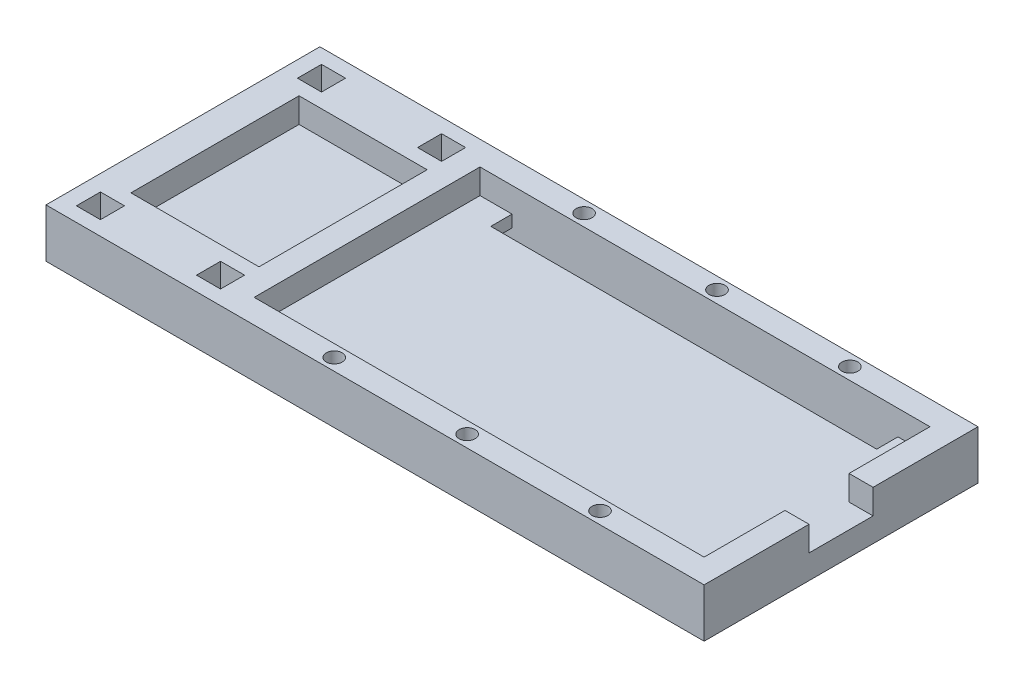
SolidWorks part; units mm, degrees
ref_plane "Front Plane" through (0, 0, 0) normal (0, 0, 1) x (1, 0, 0)
ref_plane "Top Plane" through (0, 0, 0) normal (0, 1, 0) x (1, 0, 0)
ref_plane "Right Plane" through (0, 0, 0) normal (1, 0, 0) x (0, 0, -1)
sketch "Sketch1" plane through (0, 0, 0) normal (0, 1, 0) x (1, 0, 0)
  line L1 (23.2, -12.375) -> (-23.2, -12.375)
  line L2 (23.2, -12.375) -> (23.2, 12.375)
  line L3 (23.2, 12.375) -> (-23.2, 12.375)
  line L4 (-23.2, -12.375) -> (-23.2, 12.375)
  line L5 (23.2, -12.375) -> (-23.2, 12.375) construction
  line L6 (23.2, 12.375) -> (-23.2, -12.375) construction
  point P0 (0, 0)
  dimension "D1" = 24.75
  dimension "D2" = 46.4
extrude "Boss-Extrude1" add sketch "Sketch1" along normal blind 5.9
sketch "Sketch2" plane through (0, 5.9, 0) normal (0, 1, 0) x (1, 0, 0)
  line L0 (23.2, 0) -> (23.2, 11.45)
  line L1 (23.2, -12.375) -> (23.2, 12.375) construction
  line L2 (23.2, 0) -> (23.2, -11.45)
  line L3 (23.2, -11.45) -> (23.2, 11.45)
  line L4 (23.2, -11.45) -> (-23.2, -11.45)
  line L5 (23.2, 11.45) -> (-23.2, 11.45)
  line L6 (-23.2, -11.45) -> (-23.2, 11.45)
  line M4 (-23.2, 12.375) -> (-23.2, -12.375)
  line M6 (23.2, -12.375) -> (23.2, 12.375)
  dimension "D1" = 11.45
  dimension "D2" = 11.45
  dimension "D3" = 46.4
extrude "Boss-Extrude2" add sketch "Sketch2" along normal blind 2.5 contours L5 L4 M6 M4
sketch "Sketch3" plane through (0, 0, 0) normal (0, -1, 0) x (1, 0, 0)
  line L1 (-25, 25) -> (25, 25)
  line L2 (-25, 25) -> (-25, -25)
  line L3 (-25, -25) -> (25, -25)
  line L4 (25, 25) -> (25, -25)
  line L5 (-25, 25) -> (25, -25) construction
  line L6 (-25, -25) -> (25, 25) construction
  point P0 (0, 0)
  dimension "D1" = 50
  dimension "D2" = 50
extrude "Boss-Extrude3" add sketch "Sketch3" along normal blind 2.5
sketch "Sketch4" plane through (0, 0, 0) normal (0, 1, 0) x (1, 0, 0)
  line L1 (-23.2, 12.375) -> (-23.2, 13.175)
  line L3 (23.2, 12.375) -> (23.2, 13.175)
  line L4 (23.2, 13.175) -> (-23.2, 13.175)
  line L5 (23.2, 13.175) -> (23.2, 15.175)
  line L6 (-23.2, 13.175) -> (-23.2, 15.175)
  line L7 (23.2, 15.175) -> (-23.2, 15.175)
  line L8 (23.2, 13.175) -> (-23.2, 13.175)
  line L9 (23.2, 13.175) -> (23.2, 14.105)
  line L10 (-23.2, 13.175) -> (-23.2, 14.105)
  line L11 (23.2, 14.105) -> (-23.2, 14.105)
  dimension "D1" = 0.8
  dimension "D2" = 2
  dimension "D3" = 0.93
extrude "Boss-Extrude4" add sketch "Sketch4" along normal up to surface (5.9 mm away) contours L5 L11 L6 L4 up to face at (0, 5.9, -11.9125)
sketch "Sketch5" plane through (0, 0, 0) normal (0, 1, 0) x (1, 0, 0)
  line L0 (-23.2, -12.375) -> (-23.2, -13.175)
  line L1 (23.2, -12.375) -> (23.2, -13.175)
  line L2 (23.2, -13.175) -> (-23.2, -13.175)
  line L3 (23.2, -13.175) -> (23.2, -14.105)
  line L4 (-23.2, -13.175) -> (-23.2, -14.105)
  line L5 (23.2, -14.105) -> (-23.2, -14.105)
  dimension "D1" = 0.8
  dimension "D2" = 0.93
extrude "Boss-Extrude5" add sketch "Sketch5" along normal up to surface (5.9 mm away) contours L5 L3 L2 L4 up to face at (0, 5.9, 11.9125)
sketch "Sketch6" plane through (0, 0, 0) normal (0, 1, 0) x (1, 0, 0)
  line L0 (-23.2, 14.105) -> (23.2, 14.105)
  line L1 (-23.2, 14.105) -> (-23.2, 17.105)
  line L2 (23.2, 14.105) -> (23.2, 17.105)
  line L3 (-23.2, 17.105) -> (23.2, 17.105)
  dimension "D1" = 3
extrude "Boss-Extrude6" add sketch "Sketch6" along normal up to surface (8.4 mm away) up to face at (0, 8.4, 0)
sketch "Sketch7" plane through (0, 0, 0) normal (0, 1, 0) x (1, 0, 0)
  line L0 (23.2, -14.105) -> (-23.2, -14.105)
  line L1 (23.2, -14.105) -> (23.2, -17.105)
  line L2 (-23.2, -14.105) -> (-23.2, -17.105)
  line L3 (23.2, -17.105) -> (-23.2, -17.105)
  dimension "D1" = 3
extrude "Boss-Extrude7" add sketch "Sketch7" along normal up to surface (8.4 mm away) up to face at (0, 8.4, 0)
sketch "Sketch8" plane through (0, 8.4, 0) normal (0, 1, 0) x (1, 0, 0)
  line L0 (-23.2, 11.45) -> (-23.2, -11.45)
  line L1 (-23.2, 11.45) -> (23.2, 11.45)
  line L2 (-23.2, -11.45) -> (23.2, -11.45)
  line L3 (23.2, 11.45) -> (23.2, -11.45)
  line L4 (23.2, -11.45) -> (23.2, 11.45) construction
  dimension "D1" = 0
extrude "Boss-Extrude8" add sketch "Sketch8" along normal blind 8.4
sketch "Sketch9" plane through (0, 8.4, 0) normal (0, 1, 0) x (1, 0, 0)
  line L0 (-23.2, -14.105) -> (-23.2, -17.105)
  line L1 (-23.2, -14.105) -> (23.2, -14.105)
  line L2 (-23.2, -17.105) -> (23.2, -17.105)
  line L3 (23.2, -14.105) -> (23.2, -17.105)
  line L4 (23.2, -17.105) -> (23.2, -14.105) construction
  dimension "D1" = 0
extrude "Boss-Extrude9" add sketch "Sketch9" along normal blind 8.4
sketch "Sketch10" plane through (23.2, 0, 0) normal (1, 0, 0) x (0, 0, -1)
  line L0 (-11.45, 16.8) -> (-11.45, 5.9)
  line L1 (-11.45, 16.8) -> (11.45, 16.8)
  line L2 (-11.45, 5.9) -> (11.45, 5.9)
  line L3 (11.45, 16.8) -> (11.45, 5.9)
  line L4 (-12.375, 5.9) -> (-12.375, 0)
  line L5 (-12.375, 5.9) -> (12.375, 5.9)
  line L6 (-12.375, 0) -> (12.375, 0)
  line L7 (12.375, 5.9) -> (12.375, 0)
  line L8 (12.375, 5.9) -> (12.375, 0) construction
  line L9 (11.45, 16.8) -> (11.45, 5.9) construction
  line M3 (-12.375, 0) -> (12.375, 0)
  line M4 (12.375, 0) -> (12.375, 5.9)
  line M5 (12.375, 5.9) -> (11.45, 5.9)
  line M6 (11.45, 5.9) -> (11.45, 16.8)
  line M7 (11.45, 16.8) -> (-11.45, 16.8)
  line M8 (-11.45, 16.8) -> (-11.45, 5.9)
  line M9 (-11.45, 5.9) -> (-12.375, 5.9)
  line M10 (-12.375, 5.9) -> (-12.375, 0)
  dimension "D1" = 0
  dimension "D2" = 0
extrude "Boss-Extrude10" add sketch "Sketch10" along normal up to surface (1.8 mm away) contours L2 M8 M6 M7 | L2 M9 M10 M3 M4 M5 up to face at (25, -1.25, 0)
sketch "Sketch11" plane through (23.2, 0, 0) normal (1, 0, 0) x (0, 0, -1)
  line L0 (-17.105, 16.8) -> (-14.105, 16.8)
  line L1 (-17.105, 16.8) -> (-17.105, 0)
  line L2 (-14.105, 16.8) -> (-14.105, 0)
  line L3 (-17.105, 0) -> (-14.105, 0)
  line L4 (-13.175, 0) -> (-17.105, 0) construction
  line L5 (-13.175, 5.9) -> (-14.105, 5.9)
  line L6 (-13.175, 5.9) -> (-13.175, 0)
  line L7 (-14.105, 5.9) -> (-14.105, 0)
  line L8 (-13.175, 0) -> (-14.105, 0)
  line M3 (-13.175, 0) -> (-13.175, 5.9)
  line M4 (-13.175, 5.9) -> (-14.105, 5.9)
  line M5 (-14.105, 5.9) -> (-14.105, 16.8)
  line M6 (-14.105, 16.8) -> (-17.105, 16.8)
  line M7 (-17.105, 16.8) -> (-17.105, 0)
  line M8 (-17.105, 0) -> (-13.175, 0)
  dimension "D1" = 0
  dimension "D2" = 0
extrude "Boss-Extrude11" add sketch "Sketch11" along normal up to surface (1.8 mm away) contours L2 M5 M6 M7 M8 | L2 M4 M8 M3 up to face at (25, 4.35, 0)
sketch "Sketch12" plane through (0, 5.9, 0) normal (0, 1, 0) x (1, 0, 0)
  line L0 (-23.2, -11.45) -> (-23.2, -12.375)
  line L1 (-23.2, -11.45) -> (9.5, -11.45)
  line L2 (-23.2, -12.375) -> (9.5, -12.375)
  line L3 (9.5, -11.45) -> (9.5, -12.375)
  line L4 (25, -11.45) -> (25, -12.375) construction
  line L5 (-23.2, -13.175) -> (-23.2, -14.105)
  line L6 (-23.2, -13.175) -> (9.5, -13.175)
  line L7 (-23.2, -14.105) -> (9.5, -14.105)
  line L8 (9.5, -13.175) -> (9.5, -14.105)
  line L9 (25, -14.105) -> (25, -13.175) construction
  dimension "D1" = 15.5
  dimension "D2" = 15.5
extrude "Boss-Extrude12" add sketch "Sketch12" along normal blind 8.4
sketch "Sketch13" plane through (23.2, 0, 0) normal (1, 0, 0) x (0, 0, -1)
  line L0 (17.105, 8.4) -> (14.105, 8.4)
  line L1 (17.105, 8.4) -> (17.105, 0)
  line L2 (14.105, 8.4) -> (14.105, 0)
  line L3 (17.105, 0) -> (14.105, 0)
  line L4 (13.175, 0) -> (17.105, 0) construction
  line L5 (14.105, 5.9) -> (13.175, 5.9)
  line L6 (14.105, 5.9) -> (14.105, 0)
  line L7 (13.175, 5.9) -> (13.175, 0)
  line L8 (14.105, 0) -> (13.175, 0)
  line M3 (14.105, 5.9) -> (13.175, 5.9)
  line M4 (13.175, 5.9) -> (13.175, 0)
  line M5 (13.175, 0) -> (17.105, 0)
  line M6 (17.105, 0) -> (17.105, 8.4)
  line M7 (17.105, 8.4) -> (14.105, 8.4)
  line M8 (14.105, 8.4) -> (14.105, 5.9)
  dimension "D1" = 0
  dimension "D2" = 0
extrude "Boss-Extrude13" add sketch "Sketch13" along normal up to surface (1.8 mm away) contours L2 M8 M5 M6 M7 | L2 M3 M4 M5 up to face at (25, 5.4222, 4.9317)
sketch "Sketch14" plane through (0, 8.4, 0) normal (0, 1, 0) x (1, 0, 0)
  line L0 (-23.2, 17.105) -> (-23.2, 14.105)
  line L1 (-23.2, 17.105) -> (25, 17.105)
  line L2 (-23.2, 14.105) -> (25, 14.105)
  line L3 (25, 17.105) -> (25, 14.105)
  line L4 (25, 14.105) -> (25, 17.105) construction
  dimension "D1" = 0
extrude "Boss-Extrude14" add sketch "Sketch14" along normal blind 8.4
sketch "Sketch15" plane through (0, 5.9, 0) normal (0, 1, 0) x (1, 0, 0)
  line L0 (25, 14.105) -> (25, 13.175)
  line L1 (25, 14.105) -> (-7.7, 14.105)
  line L2 (25, 13.175) -> (-7.7, 13.175)
  line L3 (-7.7, 14.105) -> (-7.7, 13.175)
  line L4 (-23.2, 13.175) -> (-23.2, 14.105) construction
  line L5 (25, 12.375) -> (25, 11.45)
  line L6 (25, 12.375) -> (-7.7, 12.375)
  line L7 (25, 11.45) -> (-7.7, 11.45)
  line L8 (-7.7, 12.375) -> (-7.7, 11.45)
  line L9 (-23.2, 12.375) -> (-23.2, 11.45) construction
  dimension "D1" = 15.5
  dimension "D2" = 15.5
extrude "Boss-Extrude15" add sketch "Sketch15" along normal blind 8.4
sketch "Sketch16" plane through (25, 0, 0) normal (1, 0, 0) x (0, 0, -1)
  line L0 (-12.775, 0) -> (-12.025, 0)
  line L1 (-12.375, 0) -> (-13.175, 0) construction
  line L2 (-12.775, 0) -> (-13.525, 0)
  line L3 (-12.025, 0) -> (-13.525, 0)
  line L4 (-12.025, 0) -> (-12.025, 5.9)
  line L5 (-13.525, 0) -> (-13.525, 5.9)
  line L6 (-12.025, 5.9) -> (-13.525, 5.9)
  line L7 (-11.45, 5.9) -> (-12.375, 5.9) construction
  line M15 (-11.45, 5.9) -> (-12.375, 5.9)
  line M16 (-12.375, 5.9) -> (-12.375, 0)
  line M18 (-13.175, 0) -> (-13.175, 5.9)
  line M19 (-13.175, 5.9) -> (-14.105, 5.9)
  dimension "D1" = 0.75
  dimension "D2" = 0
extrude "Cut-Extrude1" cut sketch "Sketch16" against normal through all contours L0 L4 M15 M16 | L5 L2 M18 M19
sketch "Sketch18" plane through (25, 0, 0) normal (1, 0, 0) x (0, 0, -1)
  line L0 (12.775, 0) -> (13.525, 0)
  line L1 (13.175, 0) -> (12.375, 0) construction
  line L2 (12.775, 0) -> (12.025, 0)
  line L3 (12.025, 0) -> (13.525, 0)
  line L4 (12.025, 0) -> (12.025, 5.9)
  line L5 (13.525, 0) -> (13.525, 5.9)
  line L6 (12.025, 5.9) -> (13.525, 5.9)
  line L7 (12.375, 5.9) -> (11.45, 5.9) construction
  line M19 (13.175, 14.3) -> (13.175, 0)
  line M21 (12.375, 0) -> (12.375, 14.3)
  dimension "D1" = 0.75
  dimension "D2" = 0
extrude "Cut-Extrude2" cut sketch "Sketch18" against normal through all contours L6 L4 L2 M21 | L6 L0 L5 M19
sketch "Sketch20" plane through (-23.2, 0, 0) normal (-1, 0, 0) x (0, 0, 1)
  line L0 (11.45, 16.8) -> (11.45, 14.3)
  line L1 (11.45, 16.8) -> (-11.45, 16.8)
  line L2 (11.45, 14.3) -> (-11.45, 14.3)
  line L3 (-11.45, 16.8) -> (-11.45, 14.3)
  line L4 (-11.45, 16.8) -> (-11.45, 5.9) construction
  dimension "D1" = 0
extrude "Boss-Extrude17" add sketch "Sketch20" along normal blind 4
sketch "Sketch22" plane through (-27.2, 0, 0) normal (-1, 0, 0) x (0, 0, 1)
  line L0 (11.45, 16.8) -> (11.45, 14.3)
  line L1 (11.45, 16.8) -> (-11.45, 16.8)
  line L2 (11.45, 14.3) -> (-11.45, 14.3)
  line L3 (-11.45, 16.8) -> (-11.45, 14.3)
  line L4 (-11.45, 16.8) -> (-11.45, 14.3) construction
  dimension "D1" = 0
extrude "Boss-Extrude19" add sketch "Sketch22" along normal blind 3
sketch "Sketch23" plane through (0, 16.8, 0) normal (0, 1, 0) x (1, 0, 0)
  line L0 (-30.2, -11.45) -> (-30.2, 11.45)
  line L1 (-30.2, -11.45) -> (-27.2, -11.45)
  line L2 (-30.2, 11.45) -> (-27.2, 11.45)
  line L3 (-27.2, -11.45) -> (-27.2, 11.45)
  dimension "D1" = 3
extrude "Boss-Extrude20" add sketch "Sketch23" along normal blind 1.5
sketch "Sketch24" plane through (25, 0, 0) normal (1, 0, 0) x (0, 0, -1)
  line L0 (11.45, 16.8) -> (11.45, 14.3)
  line L1 (11.45, 16.8) -> (-11.45, 16.8)
  line L2 (11.45, 14.3) -> (-11.45, 14.3)
  line L3 (-11.45, 16.8) -> (-11.45, 14.3)
  line L4 (-11.45, 5.9) -> (-11.45, 16.8) construction
  dimension "D1" = 0
extrude "Boss-Extrude21" add sketch "Sketch24" along normal blind 7
sketch "Sketch25" plane through (0, 16.8, 0) normal (0, 1, 0) x (1, 0, 0)
  line L0 (32, -11.45) -> (29, -11.45)
  line L1 (32, -11.45) -> (32, 11.45)
  line L2 (29, -11.45) -> (29, 11.45)
  line L3 (32, 11.45) -> (29, 11.45)
  line L4 (-27.2, -11.45) -> (32, -11.45) construction
  line L5 (32, 11.45) -> (-27.2, 11.45) construction
  dimension "D1" = 3
  dimension "D2" = 0
extrude "Boss-Extrude22" add sketch "Sketch25" along normal blind 3
sketch "Sketch27" plane through (0, 16.8, 0) normal (0, 1, 0) x (1, 0, 0)
  line L0 (25, 17.105) -> (25, 14.105)
  line L1 (25, 17.105) -> (-23.2, 17.105)
  line L2 (25, 14.105) -> (-23.2, 14.105)
  line L3 (-23.2, 17.105) -> (-23.2, 14.105)
  line L4 (-23.2, 17.105) -> (-23.2, 14.105) construction
  line L5 (25, -14.105) -> (25, -17.105)
  line L6 (25, -14.105) -> (-23.2, -14.105)
  line L7 (25, -17.105) -> (-23.2, -17.105)
  line L8 (-23.2, -14.105) -> (-23.2, -17.105)
  line L9 (-23.2, -14.105) -> (-23.2, -17.105) construction
  dimension "D1" = 0
  dimension "D2" = 0
extrude "Boss-Extrude23" add sketch "Sketch27" along normal blind 7
sketch "Sketch28" plane through (0, 16.8, 0) normal (0, 1, 0) x (1, 0, 0)
  line L0 (29, 11.45) -> (29, -11.45)
  line L1 (29, 11.45) -> (-27.2, 11.45)
  line L2 (29, -11.45) -> (-27.2, -11.45)
  line L3 (-27.2, 11.45) -> (-27.2, -11.45)
  line L4 (-27.2, -11.45) -> (-27.2, 11.45) construction
  dimension "D1" = 0
extrude "Boss-Extrude24" add sketch "Sketch28" along normal blind 7
sketch "Sketch29" plane through (0, 18.3, 0) normal (0, 1, 0) x (1, 0, 0)
  line L0 (-30.2, 11.45) -> (-27.2, 11.45)
  line L1 (-30.2, 11.45) -> (-30.2, -11.45)
  line L2 (-27.2, 11.45) -> (-27.2, -11.45)
  line L3 (-30.2, -11.45) -> (-27.2, -11.45)
  line L4 (-30.2, -11.45) -> (-27.2, -11.45) construction
  point P8 (-28.7, -11.45)
  dimension "D1" = 0
extrude "Boss-Extrude25" add sketch "Sketch29" along normal blind 7
sketch "Sketch30" plane through (0, 19.8, 0) normal (0, 1, 0) x (1, 0, 0)
  line L0 (32, 11.45) -> (29, 11.45)
  line L1 (32, 11.45) -> (32, -11.45)
  line L2 (29, 11.45) -> (29, -11.45)
  line L3 (32, -11.45) -> (29, -11.45)
  line L4 (29, -11.45) -> (32, -11.45) construction
  dimension "D1" = 0
extrude "Boss-Extrude26" add sketch "Sketch30" along normal blind 7
sketch "Sketch31" plane through (0, 0, -11.45) normal (0, 0, -1) x (-1, 0, 0)
  line L0 (30.2, 14.3) -> (23.2, 14.3)
  line L1 (30.2, 14.3) -> (30.2, 20.8)
  line L2 (23.2, 14.3) -> (23.2, 20.8)
  line L3 (30.2, 20.8) -> (23.2, 20.8)
  line L4 (-29, 23.8) -> (27.2, 23.8) construction
  dimension "D1" = 3
extrude "Cut-Extrude3" cut sketch "Sketch31" against normal through all
sketch "Sketch32" plane through (0, 0, 11.45) normal (0, 0, 1) x (1, 0, 0)
  line L0 (25, 14.3) -> (32, 14.3)
  line L1 (25, 14.3) -> (25, 20.8)
  line L2 (32, 14.3) -> (32, 20.8)
  line L3 (25, 20.8) -> (32, 20.8)
  line L4 (-27.2, 23.8) -> (29, 23.8) construction
  dimension "D1" = 3
extrude "Cut-Extrude4" cut sketch "Sketch32" against normal through all
sketch "Sketch33" plane through (-23.2, 0, 0) normal (-1, 0, 0) x (0, 0, 1)
  line L0 (-14.105, 0) -> (-11.445, 0)
  line L1 (-14.105, 0) -> (-14.105, 2.66)
  line L2 (-11.445, 0) -> (-11.445, 2.66)
  line L3 (-14.105, 2.66) -> (-11.445, 2.66)
  line L5 (25, 0) -> (-25, 0) construction
  line L6 (-14.105, 23.8) -> (-14.105, 5.9) construction
  dimension "D1" = 2.66
  dimension "D2" = 2.66
  dimension "D3" = 0
  dimension "D4" = 0
extrude "Cut-Extrude5" cut sketch "Sketch33" against normal through all
sketch "Sketch34" plane through (-23.2, 0, 0) normal (-1, 0, 0) x (0, 0, 1)
  line L0 (11.445, 0) -> (14.105, 0)
  line L1 (11.445, 0) -> (11.445, 2.66)
  line L2 (14.105, 0) -> (14.105, 2.66)
  line L3 (11.445, 2.66) -> (14.105, 2.66)
  line L4 (25, 0) -> (-25, 0) construction
  line L5 (14.105, 23.8) -> (14.105, 14.3) construction
  dimension "D1" = 2.66
  dimension "D2" = 2.66
  dimension "D3" = 0
  dimension "D4" = 0
extrude "Cut-Extrude6" cut sketch "Sketch34" against normal through all
sketch "Sketch35" plane through (0, 26.8, 0) normal (0, 1, 0) x (1, 0, 0)
  line L0 (29, 11.45) -> (32, 11.45)
  line L1 (29, 11.45) -> (29, -11.45)
  line L2 (32, 11.45) -> (32, -11.45)
  line L3 (29, -11.45) -> (32, -11.45)
  line L4 (29, -11.45) -> (32, -11.45) construction
  line L6 (37.3606, -4) -> (26.6394, -4)
  line L7 (37.3606, -4) -> (37.3606, 4)
  line L8 (37.3606, 4) -> (26.6394, 4)
  line L9 (26.6394, -4) -> (26.6394, 4)
  line L10 (37.3606, -4) -> (26.6394, 4) construction
  line L11 (37.3606, 4) -> (26.6394, -4) construction
  point P8 (32, 0)
  dimension "D1" = 0
  dimension "D2" = 8
extrude "Cut-Extrude7" cut sketch "Sketch35" against normal up to surface (3 mm away) contours L2 L8 L1 L6 up to face at (0.9, 23.8, 0)
sketch "Sketch36" plane through (0, 25.3, 0) normal (0, 1, 0) x (1, 0, 0)
  line L0 (-30.2, 11.45) -> (-27.2, 11.45)
  line L1 (-30.2, 11.45) -> (-30.2, -11.45)
  line L2 (-27.2, 11.45) -> (-27.2, -11.45)
  line L3 (-30.2, -11.45) -> (-27.2, -11.45)
  line L4 (-30.2, -11.45) -> (-27.2, -11.45) construction
  dimension "D1" = 0
extrude "Boss-Extrude27" add sketch "Sketch36" along normal up to surface (1.5 mm away) up to face at (30.5, 26.8, 7.725)
sketch "Sketch38" plane through (0, 23.8, 0) normal (0, 1, 0) x (1, 0, 0)
  line L0 (-23.2, -14.105) -> (-23.2, -17.105)
  line L1 (-23.2, -14.105) -> (25, -14.105)
  line L2 (-23.2, -17.105) -> (25, -17.105)
  line L3 (25, -14.105) -> (25, -17.105)
  line L4 (25, -17.105) -> (25, -14.105) construction
  dimension "D1" = 0
extrude "Boss-Extrude28" add sketch "Sketch38" along normal blind 3.1
sketch "Sketch39" plane through (0, 23.8, 0) normal (0, 1, 0) x (1, 0, 0)
  line L0 (-23.2, 17.105) -> (-23.2, 14.105)
  line L1 (-23.2, 17.105) -> (25, 17.105)
  line L2 (-23.2, 14.105) -> (25, 14.105)
  line L3 (25, 17.105) -> (25, 14.105)
  line L4 (25, 14.105) -> (25, 17.105) construction
  dimension "D1" = 0
extrude "Boss-Extrude29" add sketch "Sketch39" along normal blind 3.1
sketch "Sketch40" plane through (0, 26.8, 0) normal (0, 1, 0) x (1, 0, 0)
  line L0 (29, 4) -> (32, 4)
  line L1 (29, 4) -> (29, 11.45)
  line L2 (32, 4) -> (32, 11.45)
  line L3 (29, 11.45) -> (32, 11.45)
  line L4 (32, 11.45) -> (29, 11.45) construction
  line L5 (32, -11.45) -> (29, -11.45)
  line L6 (32, -11.45) -> (32, -4)
  line L7 (29, -11.45) -> (29, -4)
  line L8 (32, -4) -> (29, -4)
  line L9 (32, -4) -> (29, -4) construction
  dimension "D1" = 0
  dimension "D2" = 0
extrude "Boss-Extrude30" add sketch "Sketch40" along normal blind 0.1
sketch "Sketch41" plane through (0, 26.8, 0) normal (0, 1, 0) x (1, 0, 0)
  line L0 (-30.2, -11.45) -> (-27.2, -11.45)
  line L1 (-30.2, -11.45) -> (-30.2, 11.45)
  line L2 (-27.2, -11.45) -> (-27.2, 11.45)
  line L3 (-30.2, 11.45) -> (-27.2, 11.45)
  line L4 (-30.2, 11.45) -> (-27.2, 11.45) construction
  dimension "D1" = 0
extrude "Boss-Extrude31" add sketch "Sketch41" along normal blind 0.1
sketch "Sketch42" plane through (0, 26.9, 0) normal (0, 1, 0) x (1, 0, 0)
  line L0 (25, 14.105) -> (25, 17.105) construction
  line L1 (-23.2, -17.105) -> (25, -17.105) construction
  line L2 (-23.2, -14.105) -> (-23.2, -17.105) construction
  line L3 (-23.2, 17.105) -> (-23.2, 14.105) construction
  line L4 (25, 17.105) -> (-23.2, 17.105) construction
  line L5 (25, -17.105) -> (25, -14.105) construction
  line L6 (25, -14.105) -> (-23.2, -14.105) construction
  line L7 (-23.2, 14.105) -> (25, 14.105) construction
  circle A0 centre (-15.7, -15.605) radius 1
  circle A1 centre (-15.7, 15.605) radius 1
  circle A2 centre (17.5, -15.605) radius 1
  circle A3 centre (17.5, 15.605) radius 1
  circle A4 centre (0.9, -15.605) radius 1
  circle A5 centre (0.9, 15.605) radius 1
  dimension "D1" = 2
  dimension "D2" = 1.5
  dimension "D4" = 2
  dimension "D5" = 7.5
  dimension "D6" = 1.5
  dimension "D7" = 2
  dimension "D8" = 2
  dimension "D9" = 7.5
  dimension "D10" = 7.5
  dimension "D11" = 33.2
  dimension "D12" = 2
  dimension "D13" = 1.5
  dimension "D14" = 16.6
  dimension "D15" = 2
  dimension "D16" = 16.6
  dimension "D17" = 1.5
  dimension "D3" = 7.5
sketch "Sketch43" plane through (0, 0, 11.45) normal (0, 0, 1) x (1, 0, 0)
  line L0 (-30.2, 26.9) -> (-27.2, 26.9)
  line L1 (-30.2, 26.9) -> (-30.2, 20.8)
  line L2 (-27.2, 26.9) -> (-27.2, 20.8)
  line L3 (-30.2, 20.8) -> (-27.2, 20.8)
  line L4 (-23.2, 20.8) -> (-30.2, 20.8) construction
  dimension "D1" = 0
extrude "Boss-Extrude32" add sketch "Sketch43" along normal up to surface (5.655 mm away) up to face at (0.9, 13.45, 17.105)
sketch "Sketch44" plane through (-27.2, 0, 0) normal (1, 0, 0) x (0, 0, -1)
  line L0 (-17.105, 26.9) -> (-17.105, 20.8)
  line L1 (-17.105, 26.9) -> (-14.105, 26.9)
  line L2 (-17.105, 20.8) -> (-14.105, 20.8)
  line L3 (-14.105, 26.9) -> (-14.105, 20.8)
  line L4 (-14.105, 26.9) -> (-14.105, 14.3) construction
  dimension "D1" = 0
extrude "Boss-Extrude33" add sketch "Sketch44" along normal up to surface (4 mm away) up to face at (-23.2, 9.952, 14.403)
sketch "Sketch45" plane through (0, 0, -11.45) normal (0, 0, -1) x (-1, 0, 0)
  line L0 (30.2, 26.9) -> (27.2, 26.9)
  line L1 (30.2, 26.9) -> (30.2, 20.8)
  line L2 (27.2, 26.9) -> (27.2, 20.8)
  line L3 (30.2, 20.8) -> (27.2, 20.8)
  line L4 (30.2, 20.8) -> (23.2, 20.8) construction
  dimension "D1" = 0
extrude "Boss-Extrude34" add sketch "Sketch45" along normal up to surface (5.655 mm away) up to face at (0.9, 13.45, -17.105)
sketch "Sketch46" plane through (-27.2, 0, 0) normal (1, 0, 0) x (0, 0, -1)
  line L0 (17.105, 20.8) -> (17.105, 26.9)
  line L1 (17.105, 20.8) -> (14.105, 20.8)
  line L2 (17.105, 26.9) -> (14.105, 26.9)
  line L3 (14.105, 20.8) -> (14.105, 26.9)
  line L4 (14.105, 26.9) -> (14.105, 5.9) construction
  dimension "D1" = 0
extrude "Boss-Extrude35" add sketch "Sketch46" along normal up to surface (4 mm away) up to face at (-23.2, 8.865, -14.71)
sketch "Sketch47" plane through (0, 0, -11.45) normal (0, 0, -1) x (-1, 0, 0)
  line L0 (-29, 26.9) -> (-32, 26.9)
  line L1 (-29, 26.9) -> (-29, 20.8)
  line L2 (-32, 26.9) -> (-32, 20.8)
  line L3 (-29, 20.8) -> (-32, 20.8)
  line L4 (-32, 20.8) -> (-25, 20.8) construction
  dimension "D1" = 0
extrude "Boss-Extrude36" add sketch "Sketch47" along normal up to surface (5.655 mm away) up to face at (-9.4667, 15.9, -17.105)
sketch "Sketch48" plane through (29, 0, 0) normal (-1, 0, 0) x (0, 0, 1)
  line L0 (-17.105, 26.9) -> (-17.105, 20.8)
  line L1 (-17.105, 26.9) -> (-14.105, 26.9)
  line L2 (-17.105, 20.8) -> (-14.105, 20.8)
  line L3 (-14.105, 26.9) -> (-14.105, 20.8)
  line L4 (-14.105, 14.3) -> (-14.105, 26.9) construction
  dimension "D1" = 0
extrude "Boss-Extrude37" add sketch "Sketch48" along normal up to surface (4 mm away) up to face at (25, 7.4967, -1.4194)
sketch "Sketch49" plane through (0, 0, 11.45) normal (0, 0, 1) x (1, 0, 0)
  line L0 (32, 26.9) -> (29, 26.9)
  line L1 (32, 26.9) -> (32, 20.8)
  line L2 (29, 26.9) -> (29, 20.8)
  line L3 (32, 20.8) -> (29, 20.8)
  line L4 (32, 20.8) -> (25, 20.8) construction
  dimension "D1" = 0
extrude "Boss-Extrude38" add sketch "Sketch49" along normal up to surface (5.655 mm away) up to face at (-9.4667, 15.9, 17.105)
sketch "Sketch50" plane through (29, 0, 0) normal (-1, 0, 0) x (0, 0, 1)
  line L0 (17.105, 26.9) -> (17.105, 20.8)
  line L1 (17.105, 26.9) -> (14.105, 26.9)
  line L2 (17.105, 20.8) -> (14.105, 20.8)
  line L3 (14.105, 26.9) -> (14.105, 20.8)
  line L4 (14.105, 5.9) -> (14.105, 26.9) construction
  dimension "D1" = 0
extrude "Boss-Extrude39" add sketch "Sketch50" along normal blind 4
sketch "Sketch51" plane through (-23.2, 0, 0) normal (-1, 0, 0) x (0, 0, 1)
  line L0 (-17.105, 20.8) -> (17.105, 20.8)
  line L1 (-17.105, 20.8) -> (-17.105, -9.7446)
  line L2 (17.105, 20.8) -> (17.105, -9.7446)
  line L3 (-17.105, -9.7446) -> (17.105, -9.7446)
extrude "Cut-Extrude9" cut sketch "Sketch51" against normal through all
sketch "Sketch52" plane through (25, 0, 0) normal (1, 0, 0) x (0, 0, -1)
  line L1 (32.5447, -3.9163) -> (-30.6291, -3.9163)
  line L2 (32.5447, -3.9163) -> (32.5447, 4.1015)
  line L3 (32.5447, 4.1015) -> (-30.6291, 4.1015)
  line L4 (-30.6291, -3.9163) -> (-30.6291, 4.1015)
extrude "Cut-Extrude10" cut sketch "Sketch52" against normal through all
sketch "Sketch53" plane through (-30.2, 0, 0) normal (-1, 0, 0) x (0, 0, 1)
  line L0 (0, 20.8) -> (10.5, 20.8)
  line L1 (17.105, 20.8) -> (-17.105, 20.8) construction
  line L2 (0, 20.8) -> (-10.5, 20.8)
sketch "Sketch54" plane through (0, 20.8, 0) normal (0, -1, 0) x (1, 0, 0)
  line L0 (-30.2, 10.5) -> (-30.2, -10.5)
  line L1 (-30.2, 10.5) -> (-46.2, 10.5)
  line L2 (-30.2, -10.5) -> (-46.2, -10.5)
  line L3 (-46.2, 10.5) -> (-46.2, -10.5)
  line L4 (-30.2, 0) -> (-30.2, 10.5) construction
  line L5 (-30.2, 0) -> (-30.2, -10.5) construction
  line L6 (-30.2, 17.105) -> (-30.2, -17.105) construction
  line L7 (-30.2, 17.105) -> (-30.2, -17.105)
  line L8 (-30.2, 17.105) -> (-50.2, 17.105)
  line L9 (-30.2, -17.105) -> (-50.2, -17.105)
  line L10 (-50.2, 17.105) -> (-50.2, -17.105)
  line M5 (-30.2, 17.105) -> (-30.2, -17.105)
  dimension "D1" = 16
  dimension "D2" = 20
extrude "Boss-Extrude40" add sketch "Sketch54" against normal up to surface (6.1 mm away) contours L8 L10 L9 L2 L3 L1 M5 up to face at (10.7667, 26.9, 0)
sketch "Sketch55" plane through (0, 20.8, 0) normal (0, -1, 0) x (1, 0, 0)
  line L0 (-46.2, -10.5) -> (-30.2, -10.5)
  line L1 (-46.2, -10.5) -> (-46.2, 10.5)
  line L2 (-30.2, -10.5) -> (-30.2, 10.5)
  line L3 (-46.2, 10.5) -> (-30.2, 10.5)
  line L4 (-30.2, 10.5) -> (-46.2, 10.5) construction
  dimension "D1" = 0
extrude "Boss-Extrude41" add sketch "Sketch55" against normal blind 3
sketch "Sketch56" plane through (0, 23.8, 0) normal (0, 1, 0) x (1, 0, 0)
  line L0 (-30.2, 10.5) -> (-32.86, 10.5)
  line L1 (-30.2, 10.5) -> (-30.2, -10.5)
  line L2 (-32.86, 10.5) -> (-32.86, -10.5)
  line L3 (-30.2, -10.5) -> (-32.86, -10.5)
  line L4 (-46.2, 10.5) -> (-30.2, 10.5) construction
  line L5 (-46.2, -10.5) -> (-30.2, -10.5) construction
  dimension "D1" = 0
  dimension "D2" = 2.66
extrude "Cut-Extrude11" cut sketch "Sketch56" against normal through all
sketch "Sketch58" plane through (0, 23.8, 0) normal (0, 1, 0) x (1, 0, 0)
  line L0 (-46.2, 10.5) -> (-30.2, 10.5) construction
  line L1 (-46.2, 10.5) -> (-46.2, -10.5) construction
  line L2 (-32.86, -10.5) -> (-46.2, -10.5) construction
  line L3 (-46.2, -10.5) -> (-46.2, 10.5) construction
  circle A0 centre (-43.7, 7.9) radius 1.4
  circle A1 centre (-43.7, -7.9) radius 1.4
  dimension "D1" = 2.8
  dimension "D2" = 2.8
  dimension "D4" = 2.5
  dimension "D5" = 2.6
  dimension "D6" = 2.5
  dimension "D3" = 2.6
sketch "Sketch59" plane through (-27.2, 0, 0) normal (1, 0, 0) x (0, 0, -1)
  line L0 (14.105, 20.8) -> (14.105, 23.8)
  line L1 (14.105, 20.8) -> (11.45, 20.8)
  line L2 (14.105, 23.8) -> (11.45, 23.8)
  line L3 (11.45, 20.8) -> (11.45, 23.8)
  line L4 (14.105, 26.9) -> (14.105, 20.8) construction
  line L5 (11.45, 23.8) -> (-11.45, 23.8) construction
  line L6 (11.45, 23.8) -> (11.45, 20.8) construction
  dimension "D1" = 0
  dimension "D2" = 0
extrude "Boss-Extrude44" add sketch "Sketch59" along normal blind 4
sketch "Sketch60" plane through (-27.2, 0, 0) normal (1, 0, 0) x (0, 0, -1)
  line L0 (-14.105, 20.8) -> (-14.105, 23.8)
  line L1 (-14.105, 20.8) -> (-11.45, 20.8)
  line L2 (-14.105, 23.8) -> (-11.45, 23.8)
  line L3 (-11.45, 20.8) -> (-11.45, 23.8)
  line L4 (-14.105, 20.8) -> (-14.105, 26.9) construction
  line L5 (-11.45, 20.8) -> (-11.45, 23.8) construction
  line L6 (14.105, 23.8) -> (-11.45, 23.8) construction
  dimension "D1" = 0
  dimension "D2" = 0
extrude "Boss-Extrude45" add sketch "Sketch60" along normal blind 4
sketch "Sketch61" plane through (29, 0, 0) normal (-1, 0, 0) x (0, 0, 1)
  line L0 (-14.105, 20.8) -> (-14.105, 23.8)
  line L1 (-14.105, 20.8) -> (-11.45, 20.8)
  line L2 (-14.105, 23.8) -> (-11.45, 23.8)
  line L3 (-11.45, 20.8) -> (-11.45, 23.8)
  line L4 (-14.105, 20.8) -> (-14.105, 26.9) construction
  line L5 (-11.45, 20.8) -> (-11.45, 23.8) construction
  line L6 (-4, 23.8) -> (-11.45, 23.8) construction
  dimension "D1" = 0
  dimension "D2" = 0
extrude "Boss-Extrude46" add sketch "Sketch61" along normal blind 4
sketch "Sketch62" plane through (29, 0, 0) normal (-1, 0, 0) x (0, 0, 1)
  line L0 (14.105, 20.8) -> (14.105, 23.8)
  line L1 (14.105, 20.8) -> (11.45, 20.8)
  line L2 (14.105, 23.8) -> (11.45, 23.8)
  line L3 (11.45, 20.8) -> (11.45, 23.8)
  line L4 (14.105, 26.9) -> (14.105, 20.8) construction
  line L5 (11.45, 23.8) -> (4, 23.8) construction
  line L6 (11.45, 23.8) -> (11.45, 20.8) construction
  dimension "D1" = 0
  dimension "D2" = 0
extrude "Boss-Extrude47" add sketch "Sketch62" along normal blind 4
sketch "Sketch63" plane through (0, 23.8, 0) normal (0, 1, 0) x (1, 0, 0)
  line L0 (-27.2, 14.105) -> (29, 14.105) construction
  line L1 (-27.2, 14.105) -> (-27.2, -14.105) construction
  line L2 (29, -14.105) -> (-27.2, -14.105) construction
  line L3 (29, 14.105) -> (29, 4) construction
  line L4 (29, -4) -> (29, -14.105) construction
  circle A0 centre (-25, 12.005) radius 1
  circle A1 centre (-25, -12.005) radius 1
  circle A2 centre (26.95, 12.005) radius 1
  circle A3 centre (26.95, -12.005) radius 1
  dimension "D1" = 2
  dimension "D2" = 2.1
  dimension "D3" = 2.2
  dimension "D4" = 2
  dimension "D5" = 2.1
  dimension "D6" = 2.2
  dimension "D7" = 2
  dimension "D8" = 2.05
  dimension "D9" = 2.1
  dimension "D10" = 2
  dimension "D11" = 2.1
  dimension "D12" = 2.05
sketch "Sketch64" plane through (0, 26.9, 0) normal (0, 1, 0) x (1, 0, 0)
  line L0 (-48.2, 15.305) -> (-48.2, 12.305)
  line L1 (-48.2, 15.305) -> (-45.2, 15.305)
  line L2 (-48.2, 12.305) -> (-45.2, 12.305)
  line L3 (-45.2, 15.305) -> (-45.2, 12.305)
  line L4 (32, 17.105) -> (-50.2, 17.105) construction
  line L5 (-50.2, 17.105) -> (-50.2, -17.105) construction
  line L6 (-48.2, -12.305) -> (-48.2, -15.305)
  line L7 (-48.2, -12.305) -> (-45.2, -12.305)
  line L8 (-48.2, -15.305) -> (-45.2, -15.305)
  line L9 (-45.2, -12.305) -> (-45.2, -15.305)
  line L10 (-50.2, -17.105) -> (32, -17.105) construction
  line L11 (-33.2, 15.305) -> (-33.2, 12.305)
  line L12 (-33.2, 15.305) -> (-30.2, 15.305)
  line L13 (-33.2, 12.305) -> (-30.2, 12.305)
  line L14 (-30.2, 15.305) -> (-30.2, 12.305)
  line L15 (-27.2, 14.105) -> (-27.2, -14.105) construction
  line L16 (-33.2, -12.305) -> (-33.2, -15.305)
  line L17 (-33.2, -12.305) -> (-30.2, -12.305)
  line L18 (-33.2, -15.305) -> (-30.2, -15.305)
  line L19 (-30.2, -12.305) -> (-30.2, -15.305)
  line L20 (-27.2, -14.105) -> (-27.2, 14.105) construction
  dimension "D1" = 3
  dimension "D2" = 3
  dimension "D3" = 1.8
  dimension "D4" = 2
  dimension "D5" = 3
  dimension "D6" = 3
  dimension "D7" = 3
  dimension "D8" = 2
  dimension "D9" = 1.8
  dimension "D10" = 3
  dimension "D11" = 3
  dimension "D12" = 1.8
  dimension "D13" = 3
  dimension "D14" = 3
  dimension "D15" = 3
  dimension "D16" = 3
  dimension "D17" = 1.8
extrude "Cut-Extrude12" cut sketch "Sketch64" against normal blind 3
extrude "Cut-Extrude13" cut sketch "Sketch42" against normal blind 3
sketch "Sketch65" plane through (0, 20.8, 0) normal (0, -1, 0) x (1, 0, 0)
  line L0 (-32.86, -10.5) -> (-30.2, -10.5)
  line L1 (-32.86, -10.5) -> (-32.86, -14.105)
  line L2 (-30.2, -10.5) -> (-30.2, -14.105)
  line L3 (-32.86, -14.105) -> (-30.2, -14.105)
  line L4 (-23.2, -14.105) -> (25, -14.105) construction
  line L5 (-23.2, -11.45) -> (-23.2, -14.105)
  line L6 (-23.2, -11.45) -> (-30.2, -11.45)
  line L7 (-23.2, -14.105) -> (-30.2, -14.105)
  line L8 (-30.2, -11.45) -> (-30.2, -14.105)
  line L9 (-32.86, 10.5) -> (-30.2, 10.5)
  line L10 (-32.86, 10.5) -> (-32.86, 14.105)
  line L11 (-30.2, 10.5) -> (-30.2, 14.105)
  line L12 (-32.86, 14.105) -> (-30.2, 14.105)
  line L13 (25, 14.105) -> (-23.2, 14.105) construction
  line L14 (-23.2, 14.105) -> (-23.2, 11.45)
  line L15 (-23.2, 14.105) -> (-30.2, 14.105)
  line L16 (-23.2, 11.45) -> (-30.2, 11.45)
  line L17 (-30.2, 14.105) -> (-30.2, 11.45)
  line M10 (-23.2, 11.45) -> (-23.2, 14.105)
  line M14 (-23.2, -14.105) -> (-23.2, -11.45)
  line M15 (-32.86, 10.5) -> (-30.2, 10.5)
  line M17 (-30.2, -10.5) -> (-32.86, -10.5)
  dimension "D1" = 0
  dimension "D2" = 0
  dimension "D3" = 0
  dimension "D4" = 0
extrude "Cut-Extrude14" cut sketch "Sketch65" against normal blind 1.5 contours L12 L10 L11 M15 | L16 L15 L11 M10 | L1 L3 L2 M17 | L7 L6 L2 M14
